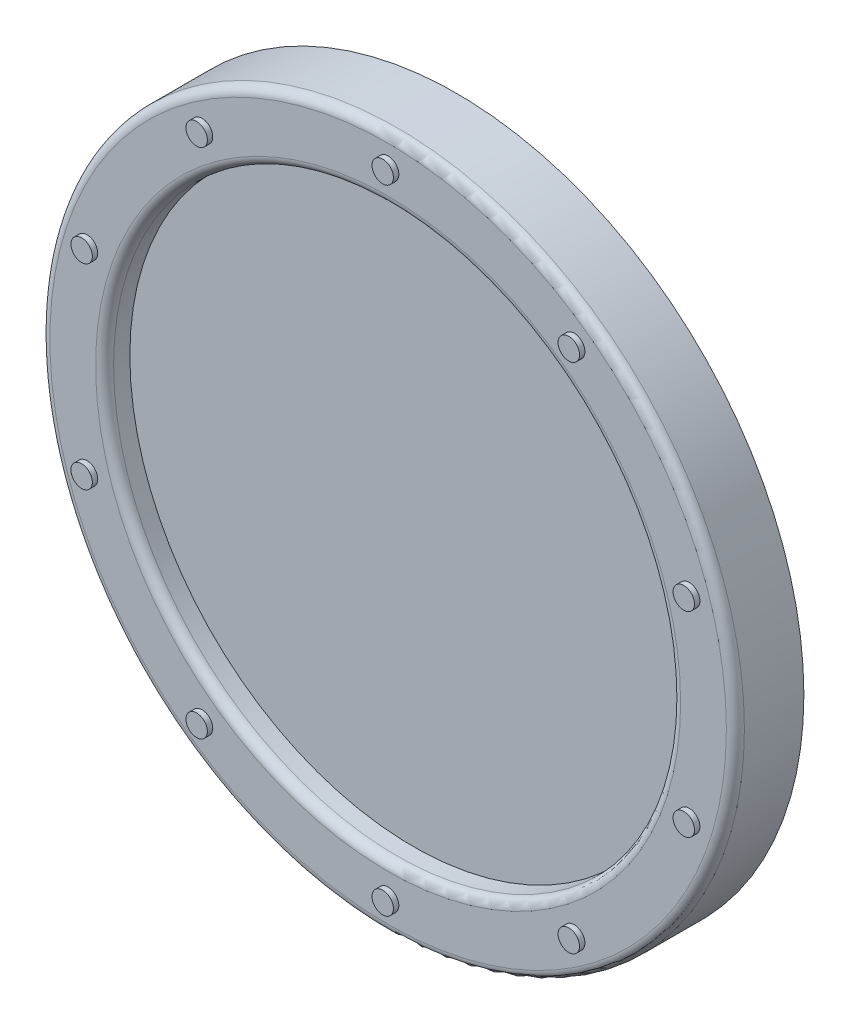
SolidWorks part; units mm, degrees
ref_plane "Front Plane" through (0, 0, 0) normal (0, 0, 1) x (1, 0, 0)
ref_plane "Top Plane" through (0, 0, 0) normal (0, 1, 0) x (1, 0, 0)
ref_plane "Right Plane" through (0, 0, 0) normal (1, 0, 0) x (0, 0, -1)
sketch "Sketch1" plane through (0, 0, 0) normal (0, 0, 1) x (1, 0, 0)
  circle A0 centre (-180.1051, 94.8006) radius 385.3863
  circle A2 centre (-180.1051, 94.8006) radius 314.62
extrude "Boss-Extrude1" add sketch "Sketch1" against normal blind 76
sketch "Sketch2" plane through (0, 0, -76) normal (0, 0, -1) x (-1, 0, 0)
  circle A0 centre (180.1051, 94.8006) radius 342.3819
extrude "Boss-Extrude2" add sketch "Sketch2" against normal blind 48 separate body
fillet "Fillet2" radius 10 1 edges at (134.515, 94.8006, 0)
fillet "Fillet3" radius 10 1 edges at (205.2812, 94.8006, 0)
sketch "Sketch3" plane through (0, 0, 0) normal (0, 0, 1) x (1, 0, 0)
  circle A0 centre (26.3833, 379.0074) radius 11.8902
  circle A1 centre (-180.1051, 446.0995) radius 11.8902
  circle A2 centre (154.0001, 203.3579) radius 11.8902
  circle A3 centre (154.0001, -13.7567) radius 11.8902
  circle A4 centre (26.3833, -189.4062) radius 11.8902
  circle A5 centre (-180.1051, -256.4983) radius 11.8902
  circle A6 centre (-386.5934, -189.4062) radius 11.8902
  circle A7 centre (-514.2102, -13.7567) radius 11.8902
  circle A8 centre (-514.2102, 203.3579) radius 11.8902
  circle A9 centre (-386.5934, 379.0074) radius 11.8902
  point P22 (-180.1051, 94.8006)
  dimension "D1" = 10
extrude "Boss-Extrude3" add sketch "Sketch3" along normal blind 6
